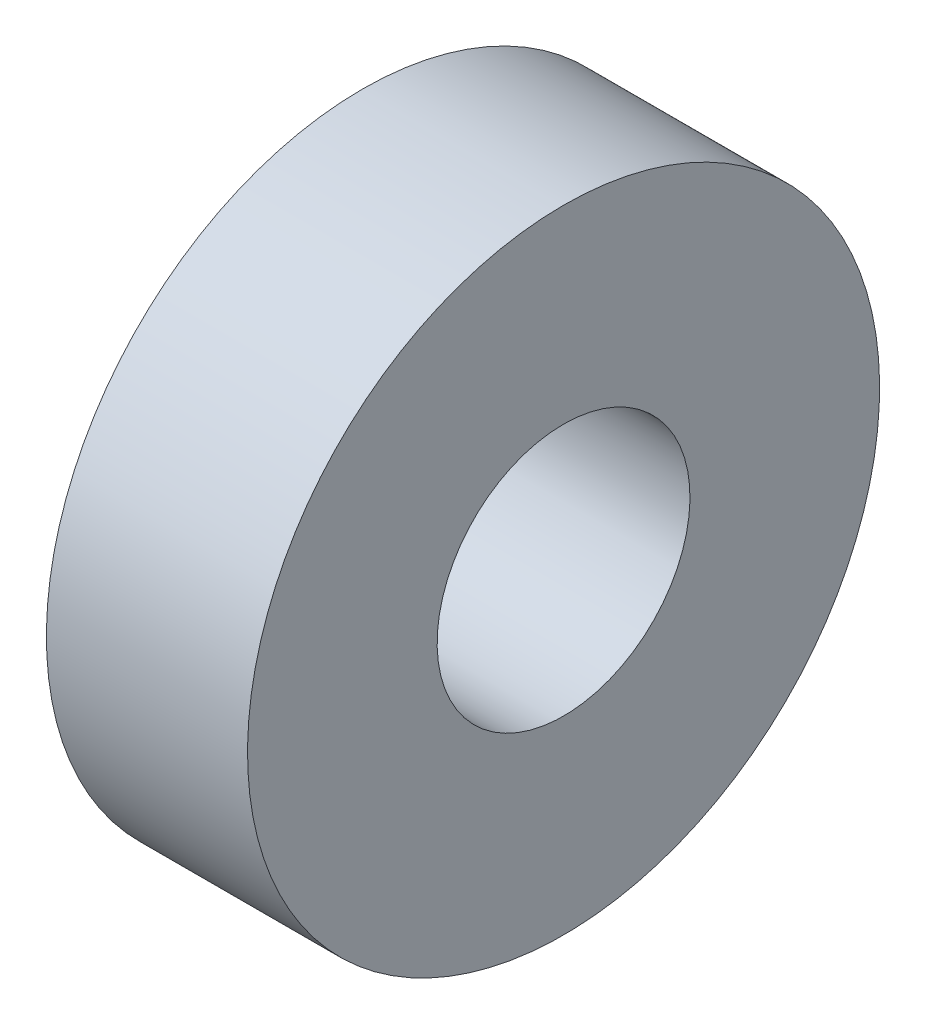
SolidWorks part; units mm, degrees
ref_plane "Front Plane" through (0, 0, 0) normal (0, 0, 1) x (1, 0, 0)
ref_plane "Top Plane" through (0, 0, 0) normal (0, 1, 0) x (1, 0, 0)
ref_plane "Right Plane" through (0, 0, 0) normal (1, 0, 0) x (0, 0, -1)
sketch "Sketch1" plane through (0, 0, 0) normal (0, 0, 1) x (1, 0, 0)
  line L0 (0, 0) -> (2000, 0) construction
  line L1 (900, 220) -> (900, 550)
  line L2 (900, 550) -> (1250, 550)
  line L3 (1250, 550) -> (1250, 220)
  line L4 (1250, 220) -> (900, 220)
revolve "Revolve1" add sketch "Sketch1" angle 360 about L0
